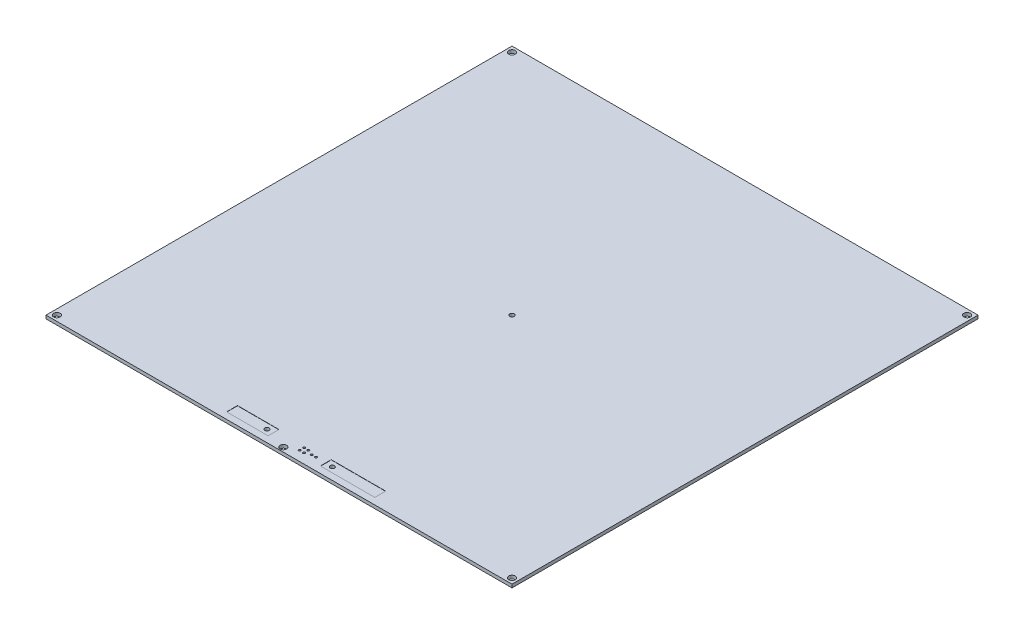
SolidWorks part; units mm, degrees
ref_plane "Ebene vorne" through (0, 0, 0) normal (0, 0, 1) x (1, 0, 0)
ref_plane "Ebene oben" through (0, 0, 0) normal (0, 1, 0) x (1, 0, 0)
ref_plane "Ebene rechts" through (0, 0, 0) normal (1, 0, 0) x (0, 0, -1)
sketch "Skizze1" plane through (0, 0, 0) normal (0, 1, 0) x (1, 0, 0)
  line L1 (107, 107) -> (-107, 107)
  line L2 (107, 107) -> (107, -107)
  line L3 (107, -107) -> (-107, -107)
  line L4 (-107, 107) -> (-107, -107)
  line L5 (107, 107) -> (-107, -107) construction
  line L6 (107, -107) -> (-107, 107) construction
  point P0 (0, 0)
  dimension "D1" = 214
  dimension "D2" = 214
extrude "Aufsatz-Linear austragen1" add sketch "Skizze1" along normal blind 1.5
sketch "Skizze2" plane through (0, 1.5, 0) normal (0, 1, 0) x (1, 0, 0)
  circle A0 centre (-104.5, 104.5) radius 1.5
  dimension "D1" = 3
  dimension "D2" = 104.5
  dimension "D3" = 104.5
extrude "Schnitt-Linear austragen1" cut sketch "Skizze2" against normal through all
mirror "Spiegeln1" about plane through (0, 0, 0) normal (0, 0, 1) of "Schnitt-Linear austragen1"
mirror "Spiegeln2" about plane through (0, 0, 0) normal (1, 0, 0) of "Spiegeln1", "Schnitt-Linear austragen1"
sketch "Skizze3" plane through (0, 1.5, 0) normal (0, 1, 0) x (1, 0, 0)
  line L0 (0, -107) -> (0, -105) construction
  line L1 (-107, -107) -> (107, -107) construction
  line L2 (7, -100.5) -> (7, -102.5) construction
  line L3 (7, -101.5) -> (9.5, -101.5) construction
  circle A0 centre (0, -105) radius 1.5
  circle A1 centre (-11, -101.5) radius 1
  circle A2 centre (19, -101.5) radius 1
  circle A3 centre (5, -100.5) radius 0.5
  circle A4 centre (5, -102.5) radius 0.5
  circle A5 centre (7, -100.5) radius 0.5
  circle A6 centre (7, -102.5) radius 0.5
  circle A7 centre (9.5, -101.5) radius 0.5
  circle A8 centre (11.5, -101.5) radius 0.5
  circle A9 centre (0, 0) radius 1.05
  dimension "D1" = 3
  dimension "D4" = 2
  dimension "D6" = 1
  dimension "D13" = 2.1
  dimension "D2" = 30
  dimension "D3" = 2
  dimension "D5" = 5.5
  dimension "D7" = 2
  dimension "D8" = 2
  dimension "D9" = 2
  dimension "D10" = 2.5
  dimension "D11" = 5
  dimension "D12" = 4.5
  dimension "D14" = 11
extrude "Schnitt-Linear austragen2" cut sketch "Skizze3" against normal through all
sketch "Skizze4" plane through (0, 1.5, 0) normal (0, 1, 0) x (1, 0, 0)
  line L0 (-11, -101.5) -> (-8, -101.5) construction
  line L1 (-27.0506, -99) -> (-8, -99)
  line L2 (-27.0506, -99) -> (-27.0506, -104)
  line L3 (-27.0506, -104) -> (-8, -104)
  line L4 (-8, -99) -> (-8, -104)
  line L5 (16, -99) -> (41, -99)
  line L6 (16, -99) -> (16, -104)
  line L7 (16, -104) -> (41, -104)
  line L8 (41, -99) -> (41, -104)
  line L9 (19, -101.5) -> (16, -101.5) construction
  dimension "D1" = 3
  dimension "D2" = 5
  dimension "D3" = 25
extrude "Schnitt-Linear austragen3" cut sketch "Skizze4" against normal blind 0.1
equation "\"X-ROD-SPACING\"=45"
equation "\"Y-ROD-SPACING\"=75"
equation "\"Z-ROD-SPACING\"=17.5"
equation "\"Y-BED-OFFSET\"=2"
equation "\"Y-BED-ROD-INSET\"=3.5"
equation "\"Y-BED-SCREW-SPACING\"=209"
equation "\"Y-BED-SCREW-CUTOUT-SLOT-HEIGHT\"=1"
equation "\"T-SLOT-NUT-FILLET-RADIUS\"=0.25"
equation "\"T-SLOT-SCREW-SHAFT-RADIUS\"=1.75"
equation "\"T-SLOT-SCREW-SHAFT-CUTOUT-LENGTH\"=10.5"
equation "\"T-SLOT-NUT-DEPTH\"=4.2"
equation "\"T-SLOT-NUT-WIDTH\"=3"
equation "\"T-SLOT-NUT-END-DISTANCE\"=8"
equation "\"ACRYLIC-THICKNESS\"=10"
equation "\"ACRYLIC-THICKNESS2\"=4.5"
equation "\"ACRYLIC-TAB-CUTOUT-SIZE\"=\"ACRYLIC-THICKNESS\"+\"ACRYLIC-TAB-TOLERANCE\"*2"
equation "\"ACRYLIC-TAB-WIDTH\"=\"ACRYLIC-THICKNESS\""
equation "\"ACRYLIC-M3-HOLE\"=3.2"
equation "\"SMOOTHROD-CAP-SCREW-DISTANCE\"=20"
equation "\"FRAME-WIDTH-INNER\"=370"
equation "\"NEMA17-HOLE-SPACING\"=31"
equation "\"NEMA17-CENTRAL-CUTOUT\"=22.5"
equation "\"Z-BRACKET-REACH\"=55"
equation "\"Z-ROD-INSET\"=16"
equation "\"TOP-BRACKET-SPACING\"=40"
equation "\"SMOOTHROD-X-LENGTH\"=350"
equation "\"SMOOTHROD-Y-LENGTH\"=350"
equation "\"SMOOTHROD-Z-LENGTH\"=350"
equation "\"SMOOTHROD-TIGHTENING-HEADROOM\"=1"
equation "\"LEADSCREW-Z-LENGTH\"=300"
equation "\"SCREW-LENGTH-FRAME\"=\"ACRYLIC-THICKNESS\" + 10"
equation "\"SCREW-LENGTH-MOTOR\"=\"ACRYLIC-THICKNESS\" + 5"
equation "\"SCREW-LENGTH-EXTRUDER\"=28"
equation "\"SCREW-HEAD-RADIUS\"=6"
equation "\"PRINTED-X-SMOOTHROD-DIAMETER\"=8.2"
equation "\"PRINTED-X-SMOOTHROD-CUTOUT\"=10"
equation "\"PRINTED-X-BASE-HEIGHT\"=10"
equation "\"PRINTED-LM8UU-CUTOUT-SIZE\"=16"
equation "\"PRINTED-LM8UU-CUTOUT-LENGTH\"=24.5"
equation "\"PRINTED-X-IDLER-HEIGHT\"=16"
equation "\"PSU-MOUNTING-WIDTH\"=95"
equation "\"PSU-MOUNTING-HEIGHT\"=177"
equation "\"Y-BELT-TO-ROD-DISTANCE\"=20"
equation "\"SPOOL-HOLDER-ROD-SPACING\"=150"
equation "\"ACRYLIC-X-CARRIAGE-WIDTH\"=55"
equation "\"ACRYLIC-X-CARRIAGE-HEIGHT\"=75"
equation "\"ACRYLIC-X-CARRIAGE-LM8UU-CUTOUT-WIDTH\"=24.25"
equation "\"ACRYLIC-X-CARRIAGE-SCREW-SPACING-X\"=15"
equation "\"ACRYLIC-X-CARRIAGE-SCREW-SPACING-Y\"=33"
equation "\"ACRYLIC-X-CARRIAGE-CENTER-TAB-SPACING\"=14"
equation "\"ACRYLIC-X-CARRIAGE-EXTRUDER-OFFSET\"=26"
equation "\"ACRYLIC-X-CARRIAGE-EXTRUDER-ANGLE\"=90"
equation "\"ACRYLIC-X-CARRIAGE-EXTRUDER-SHELF-DEPTH\"=\"ACRYLIC-X-CARRIAGE-EXTRUDER-OFFSET\" + 30"
equation "\"ACRYLIC-X-CARRIAGE-EXTRUDER-BRACE-SPACING\"=23"
equation "\"ACRYLIC-X-CARRIAGE-EXTRUDER-BRACE-TAB-OFFSET\"=20"
equation "\"ACRYLIC-X-CARRIAGE-EXTRUDER-BRACE-HEIGHT\"=35"
equation "\"ACRYLIC-X-CARRIAGE-EXTRUDER-BRACE-SCREW-SPACING\"=22"
equation "\"D2@Skizze2\"=\"Y-BED-SCREW-SPACING\"/2"
equation "\"D3@Skizze2\"=\"Y-BED-SCREW-SPACING\"/2"
